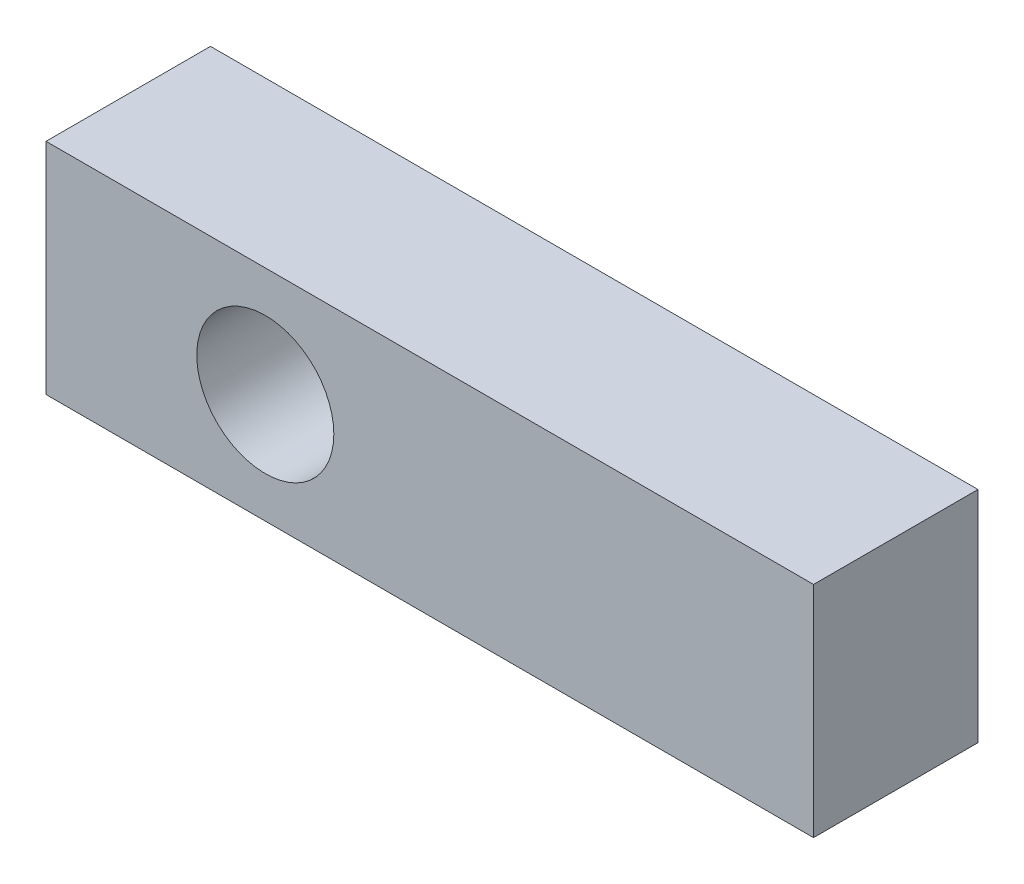
SolidWorks part; units mm, degrees
ref_plane "Přední rovina" through (0, 0, 0) normal (0, 0, 1) x (1, 0, 0)
ref_plane "Horní rovina" through (0, 0, 0) normal (0, 1, 0) x (1, 0, 0)
ref_plane "Pravá rovina" through (0, 0, 0) normal (1, 0, 0) x (0, 0, -1)
sketch "Skica1" plane through (0, 0, 0) normal (0, 0, 1) x (1, 0, 0)
  line L1 (-14, 4) -> (14, 4)
  line L2 (-14, 4) -> (-14, -4)
  line L3 (-14, -4) -> (14, -4)
  line L4 (14, 4) -> (14, -4)
  line L5 (-14, 4) -> (14, -4) construction
  line L6 (-14, -4) -> (14, 4) construction
  point P0 (0, 0)
  dimension "D1" = 28
  dimension "D2" = 8
extrude "Přidat vysunutím2" add sketch "Skica1" along normal blind 6
sketch "Skica2" plane through (0, 0, 6) normal (0, 0, 1) x (1, 0, 0)
  line L0 (-14, 4) -> (-14, -4) construction
  line L1 (-14, -4) -> (14, -4) construction
  circle A0 centre (-6, 0) radius 2.5
  dimension "D1" = 5
  dimension "D2" = 8
  dimension "D3" = 4
extrude "Odebrat vysunutím1" cut sketch "Skica2" against normal through all
